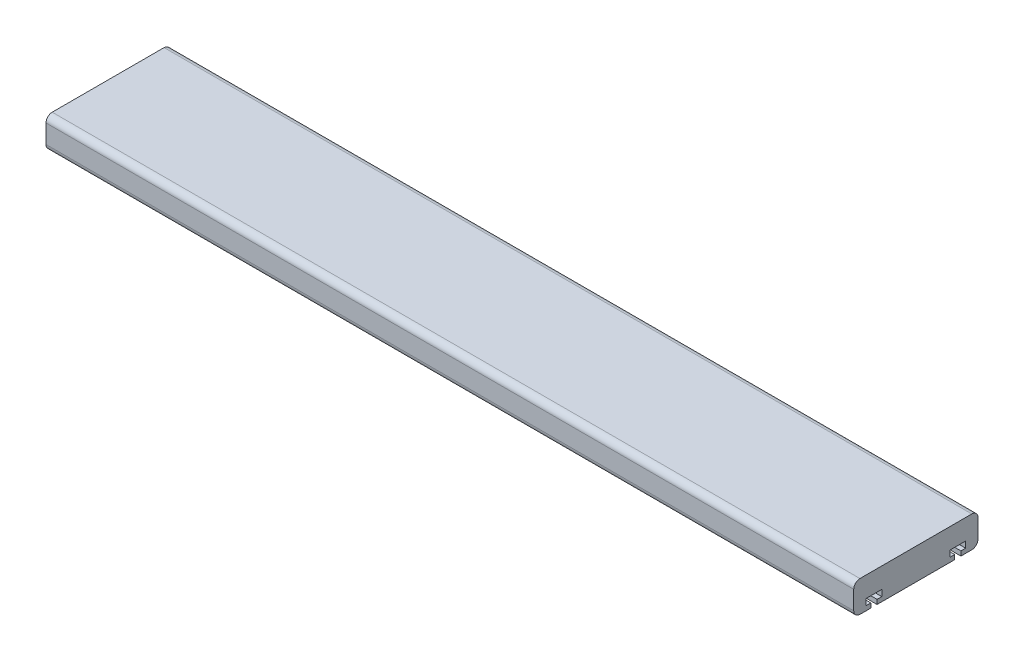
SolidWorks part; units mm, degrees
material "Commercially Pure CP-Ti UNS R50400 (SS)"
ref_plane "Front Plane" through (0, 0, 0) normal (0, 0, 1) x (1, 0, 0)
ref_plane "Top Plane" through (0, 0, 0) normal (0, 1, 0) x (1, 0, 0)
ref_plane "Right Plane" through (0, 0, 0) normal (1, 0, 0) x (0, 0, -1)
sketch "Sketch1" plane through (0, 0, 0) normal (0, 0, 1) x (1, 0, 0)
  line L1 (165.1, -6.35) -> (-165.1, -6.35)
  line L2 (165.1, -6.35) -> (165.1, 6.35)
  line L3 (165.1, 6.35) -> (-165.1, 6.35)
  line L4 (-165.1, -6.35) -> (-165.1, 6.35)
  line L5 (165.1, -6.35) -> (-165.1, 6.35) construction
  line L6 (165.1, 6.35) -> (-165.1, -6.35) construction
  point P0 (0, 0)
  dimension "D1" = 330.2
  dimension "D2" = 12.7
extrude "Boss-Extrude1" add sketch "Sketch1" along normal blind 50.8
sketch "Sketch2" plane through (-165.1, 0, 0) normal (-1, 0, 0) x (0, 0, 1)
  line L0 (41.271, -6.35) -> (41.271, -4.5096)
  line L1 (50.8, -6.35) -> (0, -6.35) construction
  line L2 (41.271, -4.5096) -> (39.3323, -4.5096)
  line L3 (39.3323, -4.5096) -> (39.3323, -1.9696)
  line L4 (39.3323, -1.9696) -> (45.7497, -1.9696)
  line L5 (45.7497, -1.9696) -> (45.7497, -4.5096)
  line L6 (45.7497, -4.5096) -> (43.811, -4.5096)
  line L7 (43.811, -4.5096) -> (43.811, -6.35)
  line L8 (41.271, -6.35) -> (43.811, -6.35)
  point P4 (42.541, -1.9696)
  point P11 (42.541, -6.35)
  dimension "D1" = 2.54
  dimension "D2" = 2.54
  dimension "D3" = 2.54
  dimension "D4" = 6.4174
  dimension "D5" = 39.3323
  dimension "D6" = 1.8404
ref_plane "Plane1" through (0, 0, 25.4) normal (0, 0, 1) x (1, 0, 0)
extrude "Cut-Extrude1" cut sketch "Sketch2" against normal up to next
mirror "Mirror1" about plane through (0, 0, 25.4) normal (0, 0, 1) of "Cut-Extrude1"
fillet "Fillet1" radius 2.54 4 edges at (0, 6.35, 0) (0, -6.35, 0) (0, -6.35, 50.8) (0, 6.35, 50.8)
